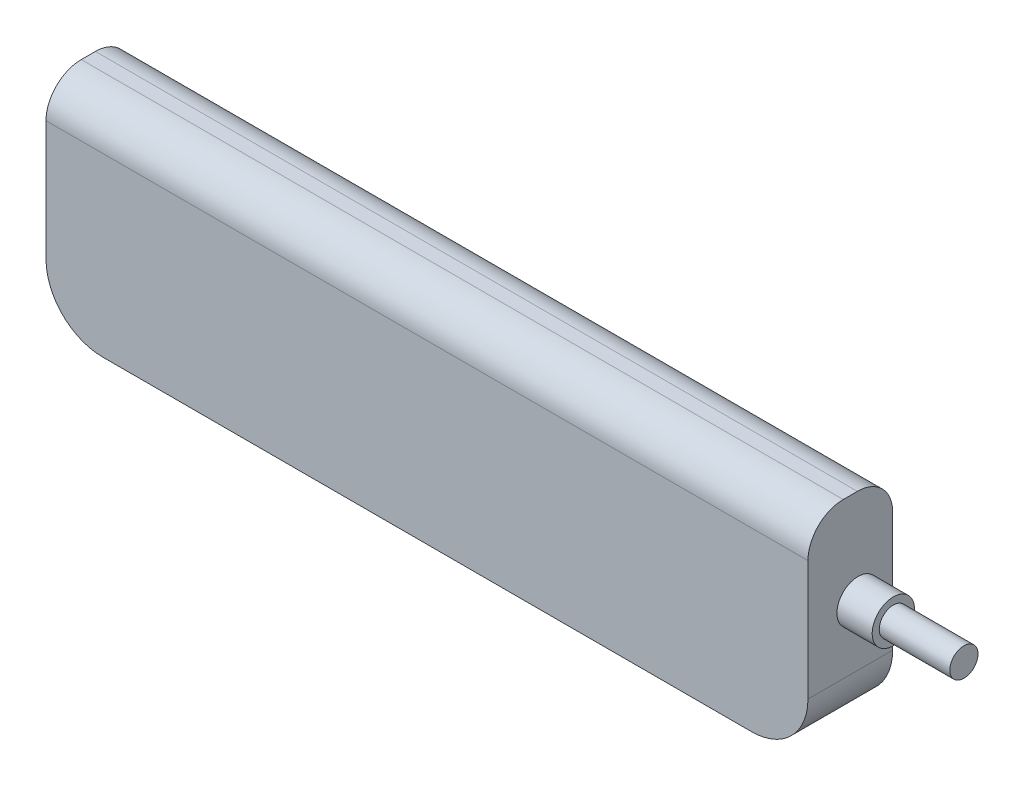
SolidWorks part; units mm, degrees
ref_plane "前视基准面" through (0, 0, 0) normal (0, 0, 1) x (1, 0, 0)
ref_plane "上视基准面" through (0, 0, 0) normal (0, 1, 0) x (1, 0, 0)
ref_plane "右视基准面" through (0, 0, 0) normal (1, 0, 0) x (0, 0, -1)
other "Configuration Table"
ref_plane "基准面1" through (0, 0, 0) normal (0, 0, -1) x (-1, 0, 0)
sketch "草图1" plane through (0, 0, 0) normal (0, 0, -1) x (-1, 0, 0)
  line L0 (-54, 15) -> (-54, -15)
  line L1 (-54, -15) -> (54, -15)
  line L2 (54, -15) -> (54, 15)
  line L3 (54, 15) -> (-54, 15)
  dimension "D1" = 108
  dimension "D2" = 30
extrude "凸台-拉伸1" add sketch "草图1" against normal blind 12
sketch "草图2" plane through (-54, 0, 0) normal (-1, 0, 0) x (0, 0, 1)
  line L0 (8.5, 10) -> (3.5, 10)
  line L1 (3.5, 10) -> (3.5, -2)
  line L2 (3.5, -2) -> (8.5, -2)
  line L3 (8.5, -2) -> (8.5, 10)
  line L4 (0, -15) -> (0, 15) construction
  line L5 (12, -15) -> (0, -15) construction
  dimension "D1" = 3.5
  dimension "D2" = 8.5
  dimension "D3" = 13
  dimension "D4" = 25
extrude "切除-拉伸1" cut sketch "草图2" against normal blind 8
sketch "草图3" plane through (-46, 0, 0) normal (-1, 0, 0) x (0, 0, 1)
  line L0 (7.3, 9) -> (8.1, 9)
  line L1 (8.1, 9) -> (8.1, -1)
  line L2 (8.1, -1) -> (7.3, -1)
  line L3 (7.3, -1) -> (7.3, 9)
  line L4 (8.5, -2) -> (8.5, 10) construction
  line L5 (8.5, 10) -> (3.5, 10) construction
  dimension "D1" = 0.4
  dimension "D2" = 1.2
  dimension "D3" = 1
  dimension "D4" = 11
extrude "凸台-拉伸2" add sketch "草图3" along normal blind 6
sketch "草图4" plane through (0, -15, 0) normal (0, -1, 0) x (1, 0, 0)
  line L0 (-40, 8.5) -> (-40, 3.5)
  line L1 (-40, 3.5) -> (-29, 3.5)
  line L2 (-29, 3.5) -> (-29, 8.5)
  line L3 (-29, 8.5) -> (-40, 8.5)
  line L4 (54, 12) -> (54, 0) construction
  line L5 (54, 0) -> (-54, 0) construction
  dimension "D1" = 83
  dimension "D2" = 94
  dimension "D3" = 3.5
  dimension "D4" = 8.5
extrude "切除-拉伸2" cut sketch "草图4" against normal blind 8
sketch "草图5" plane through (0, -7, 0) normal (0, -1, 0) x (1, 0, 0)
  line L0 (-39.5, 7.4) -> (-39.5, 8.2)
  line L1 (-39.5, 8.2) -> (-29.5, 8.2)
  line L2 (-29.5, 8.2) -> (-29.5, 7.4)
  line L3 (-29.5, 7.4) -> (-39.5, 7.4)
  line L4 (-40, 8.5) -> (-40, 3.5) construction
  line L5 (-29, 8.5) -> (-40, 8.5) construction
  dimension "D1" = 0.5
  dimension "D2" = 10.5
  dimension "D3" = 0.3
  dimension "D4" = 1.1
extrude "凸台-拉伸3" add sketch "草图5" along normal blind 6
sketch "草图6" plane through (0, -15, 0) normal (0, -1, 0) x (1, 0, 0)
  line L0 (-9, 8.5) -> (-9, 3.5)
  line L1 (-9, 3.5) -> (2, 3.5)
  line L2 (2, 3.5) -> (2, 8.5)
  line L3 (2, 8.5) -> (-9, 8.5)
  line L4 (-40, 8.5) -> (-40, 3.5) construction
  line L5 (-29, 8.5) -> (-40, 8.5) construction
  dimension "D1" = 31
  dimension "D2" = 42
  dimension "D3" = 5
extrude "切除-拉伸3" cut sketch "草图6" against normal blind 8
sketch "草图7" plane through (0, -7, 0) normal (0, -1, 0) x (1, 0, 0)
  line L0 (-8.5, 7.4) -> (-8.5, 8.2)
  line L1 (-8.5, 8.2) -> (1.5, 8.2)
  line L2 (1.5, 8.2) -> (1.5, 7.4)
  line L3 (1.5, 7.4) -> (-8.5, 7.4)
  line L4 (-9, 8.5) -> (-9, 3.5) construction
  line L5 (2, 8.5) -> (-9, 8.5) construction
  dimension "D1" = 0.5
  dimension "D2" = 10.5
  dimension "D3" = 0.3
  dimension "D4" = 1.1
extrude "凸台-拉伸4" add sketch "草图7" along normal blind 6
sketch "草图8" plane through (0, -15, 0) normal (0, -1, 0) x (1, 0, 0)
  line L0 (12, 8.5) -> (12, 3.5)
  line L1 (12, 3.5) -> (23, 3.5)
  line L2 (23, 3.5) -> (23, 8.5)
  line L3 (23, 8.5) -> (12, 8.5)
  line L4 (2, 3.5) -> (2, 8.5) construction
  line L5 (2, 8.5) -> (-9, 8.5) construction
  dimension "D1" = 10
  dimension "D2" = 21
  dimension "D3" = 5
extrude "切除-拉伸4" cut sketch "草图8" against normal blind 8
sketch "草图9" plane through (0, -7, 0) normal (0, -1, 0) x (1, 0, 0)
  line L0 (12.5, 7.4) -> (12.5, 8.2)
  line L1 (12.5, 8.2) -> (22.5, 8.2)
  line L2 (22.5, 8.2) -> (22.5, 7.4)
  line L3 (22.5, 7.4) -> (12.5, 7.4)
  line L4 (12, 8.5) -> (12, 3.5) construction
  line L5 (23, 8.5) -> (12, 8.5) construction
  dimension "D1" = 0.5
  dimension "D2" = 10.5
  dimension "D3" = 0.3
  dimension "D4" = 1.1
extrude "凸台-拉伸5" add sketch "草图9" along normal blind 6
ref_plane "基准面2" through (0, 0, 4.8999) normal (0, 0, 1) x (1, 0, 0)
sketch "草图10" plane through (0, 0, 4.8999) normal (0, 0, 1) x (1, 0, 0)
  line L0 (54, 4.5) -> (54, 1.5)
  line L1 (54, 1.5) -> (69, 1.5)
  line L2 (69, 1.5) -> (69, 3.5)
  line L3 (69, 3.5) -> (59, 3.5)
  line L4 (59, 3.5) -> (59, 4.5)
  line L5 (59, 4.5) -> (54, 4.5)
  line L6 (54, 1.5) -> (69, 1.5) construction
  dimension "D1" = 5
  dimension "D2" = 15
  dimension "D3" = 2
  dimension "D4" = 3
revolve "旋转1" add sketch "草图10" angle 360 about L6
fillet "圆角1" radius 5 2 edges at (0, 15, 12) (0, 15, 0)
fillet "圆角2" radius 8 2 edges at (-54, -15, 6) (54, -15, 6)
